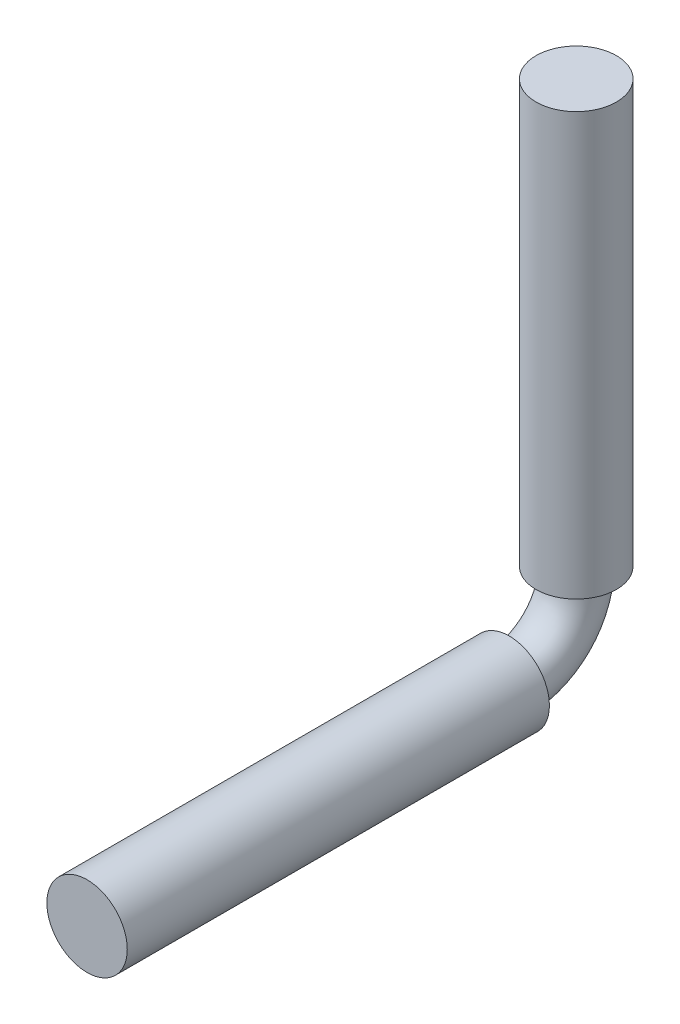
SolidWorks part; units mm, degrees
ref_plane "Front Plane" through (0, 0, 0) normal (0, 0, 1) x (1, 0, 0)
ref_plane "Top Plane" through (0, 0, 0) normal (0, 1, 0) x (1, 0, 0)
ref_plane "Right Plane" through (0, 0, 0) normal (1, 0, 0) x (0, 0, -1)
sketch "Sketch1" plane through (0, 0, 0) normal (0, 0, 1) x (1, 0, 0)
  circle A0 centre (0, 0) radius 3
  dimension "D1" = 6
extrude "Boss-Extrude1" add sketch "Sketch1" along normal blind 31.5 contours A0
sketch "Sketch4" plane through (0, 0, 0) normal (0, 0, -1) x (-1, 0, 0)
  circle A0 centre (0, 0) radius 2
  dimension "D1" = 4
sketch "Sketch5" plane through (0, 0, 0) normal (1, 0, 0) x (0, 0, -1)
  arc A0 (0, 0) -> (5, 5) centre (0, 5) ccw
  point P4 (5.2711, 4.9926)
  point P5 (0, 0)
  dimension "D1" = 5
sweep "Sweep1" add profiles "Sketch4" path "Sketch5"
sketch "Sketch9" plane through (0, 5, 0) normal (0, 1, 0) x (1, 0, 0)
  line L0 (0, 0) -> (0, 5) construction
  circle A0 centre (0, 5) radius 3
  circle A1 centre (0, 5) radius 2 construction
  point P4 (0, 0)
  point P6 (0, 5.3873)
  dimension "D1" = 6
extrude "Boss-Extrude2" add sketch "Sketch9" along normal blind 31.5
